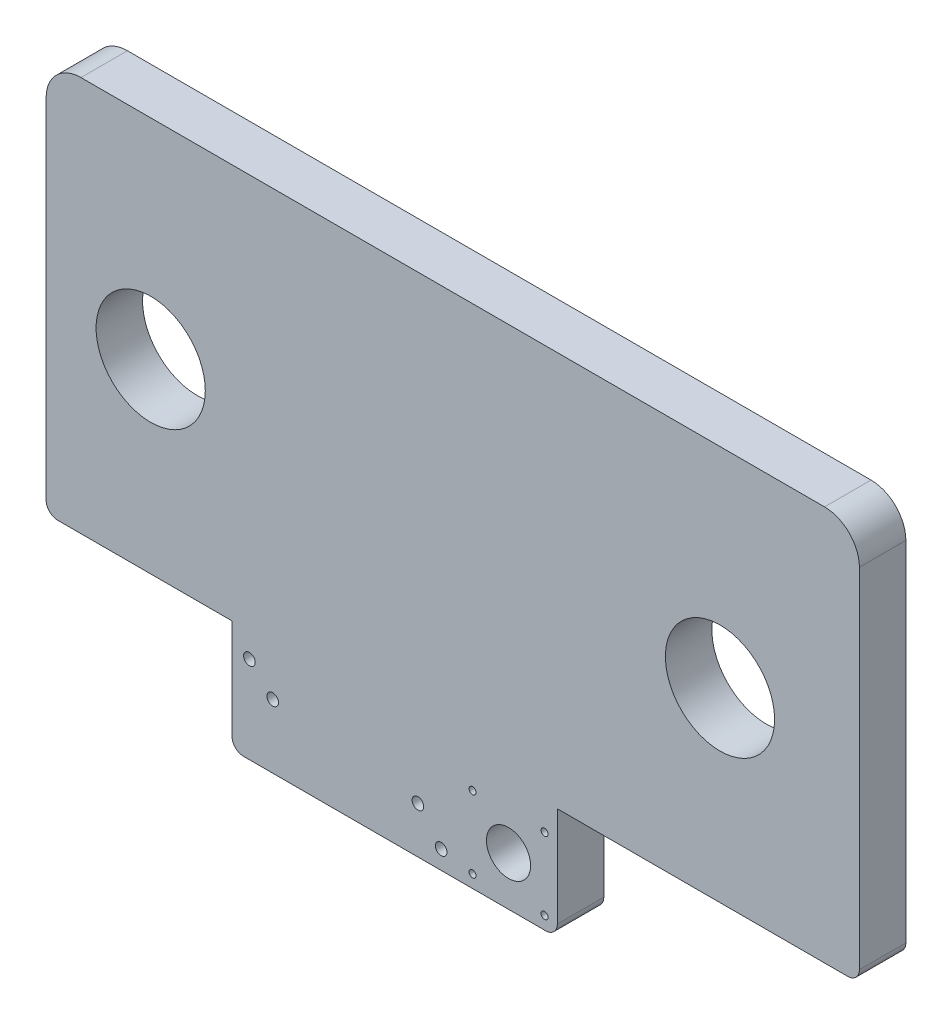
SolidWorks part; units mm, degrees
ref_plane "前视基准面" through (0, 0, 0) normal (0, 0, 1) x (1, 0, 0)
ref_plane "上视基准面" through (0, 0, 0) normal (0, 1, 0) x (1, 0, 0)
ref_plane "右视基准面" through (0, 0, 0) normal (1, 0, 0) x (0, 0, -1)
sketch "草图1" plane through (0, 0, 0) normal (0, 0, 1) x (1, 0, 0)
  line L0 (-112.1461, 163.7236) -> (237.8539, 163.7236)
  line L1 (237.8539, 163.7236) -> (237.8539, -6.2764)
  line L2 (237.8539, -6.2764) -> (107.8539, -6.2764)
  line L3 (107.8539, -6.2764) -> (107.8539, -54.2764)
  line L4 (107.8539, -54.2764) -> (-32.1461, -54.2764)
  line L5 (-32.1461, -54.2764) -> (-32.1461, -6.2764)
  line L6 (-32.1461, -6.2764) -> (-112.1461, -6.2764)
  line L7 (-112.1461, -6.2764) -> (-112.1461, 163.7236)
  circle A0 centre (177.8539, 73.7236) radius 23.5
  circle A3 centre (-67.1461, 73.7236) radius 23.5
  dimension "D7" = 47
  dimension "D12" = 80
  dimension "D13" = 47
  dimension "D1" = 350
  dimension "D2" = 170
  dimension "D3" = 170
  dimension "D4" = 140
  dimension "D6" = 48
  dimension "D8" = 90
  dimension "D9" = 60
  dimension "D10" = 90
  dimension "D11" = 45
extrude "凸台-拉伸1" add sketch "草图1" along normal blind 20
sketch "草图2" plane through (0, 0, 20) normal (0, 0, 1) x (1, 0, 0)
  line L1 (-32.1461, -54.2764) -> (107.8539, -54.2764) construction
  line L2 (-112.1461, 163.7236) -> (-112.1461, -6.2764) construction
  circle A0 centre (47.8539, -34.2764) radius 2.5
  circle A1 centre (57.8539, -46.2764) radius 2.5
  dimension "D1" = 5
  dimension "D2" = 5
  dimension "D3" = 10
  dimension "D4" = 160
  dimension "D5" = 8
  dimension "D6" = 12
extrude "切除-拉伸1" cut sketch "草图2" against normal through all
sketch "草图5" plane through (0, 0, 20) normal (0, 0, 1) x (1, 0, 0)
  line L0 (-32.1461, -6.2764) -> (-32.1461, -54.2764) construction
  line L1 (-32.1461, -54.2764) -> (107.8539, -54.2764) construction
  circle A0 centre (-24.6461, -16.7764) radius 2.5
  circle A1 centre (-14.6461, -26.7764) radius 2.5
  dimension "D1" = 5
  dimension "D2" = 5
  dimension "D3" = 10
  dimension "D4" = 10
  dimension "D5" = 7.5
  dimension "D6" = 27.5
extrude "切除-拉伸3" cut sketch "草图5" against normal through all
sketch "草图6" plane through (0, 0, 20) normal (0, 0, 1) x (1, 0, 0)
  line L0 (66.2088, -33.2764) -> (115.7442, -33.2764) construction
  line L1 (86.8539, -18.7378) -> (86.8539, -71.2329) construction
  line L2 (107.8539, -54.2764) -> (107.8539, -6.2764) construction
  line L3 (-32.1461, -54.2764) -> (107.8539, -54.2764) construction
  circle A0 centre (86.8539, -33.2764) radius 9.5
  circle A2 centre (71.3539, -17.7764) radius 1.5
  circle A3 centre (71.3539, -48.7764) radius 1.5
  circle A4 centre (102.3539, -48.7764) radius 1.5
  circle A5 centre (102.3539, -17.7764) radius 1.5
  dimension "D5" = 3
  dimension "D6" = 19
  dimension "D1" = 31
  dimension "D2" = 31
  dimension "D3" = 5.5
  dimension "D4" = 5.5
extrude "切除-拉伸4" cut sketch "草图6" against normal through all
fillet "圆角1" radius 5 1 edges at (-32.1461, -54.2764, 10)
fillet "圆角2" radius 5 1 edges at (107.8539, -54.2764, 10)
fillet "圆角3" radius 5 1 edges at (237.8539, -6.2764, 10)
fillet "圆角4" radius 5 1 edges at (-112.1461, -6.2764, 10)
fillet "圆角5" radius 15 1 edges at (-112.1461, 163.7236, 10)
fillet "圆角6" radius 15 1 edges at (237.8539, 163.7236, 10)
